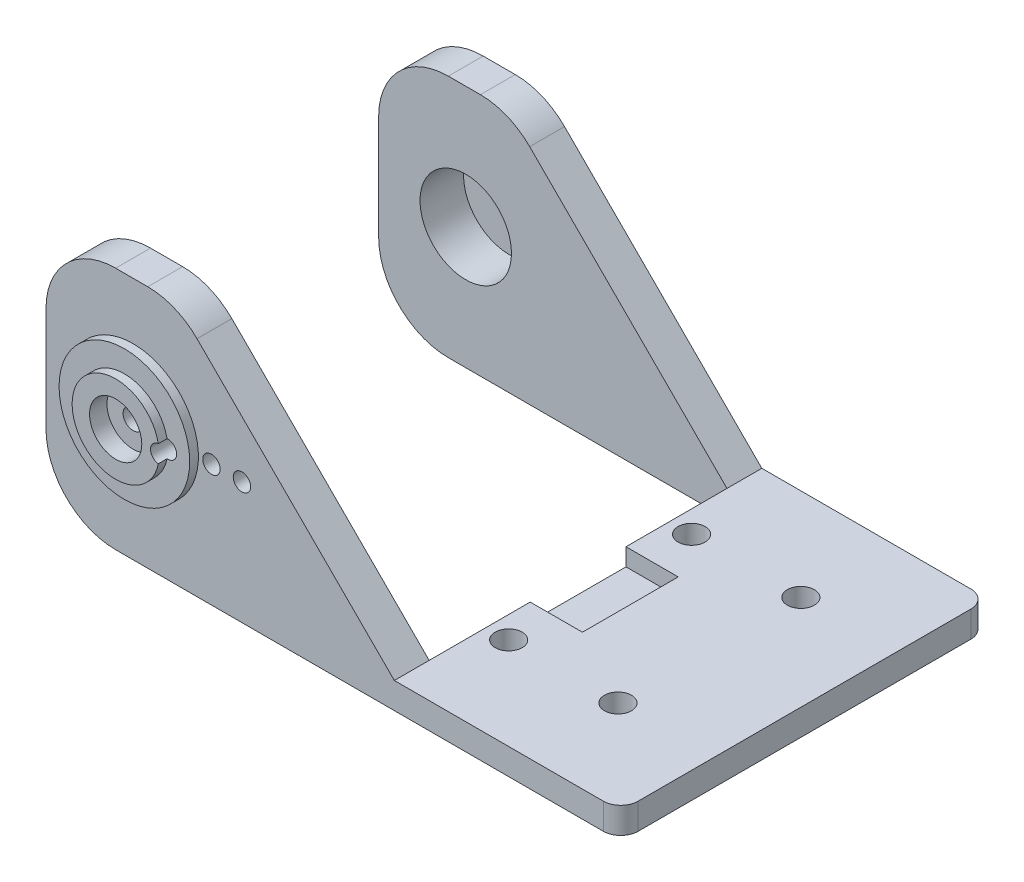
SolidWorks part; units mm, degrees
ref_plane "Front Plane" through (0, 0, 0) normal (0, 0, 1) x (1, 0, 0)
ref_plane "Top Plane" through (0, 0, 0) normal (0, 1, 0) x (1, 0, 0)
ref_plane "Right Plane" through (0, 0, 0) normal (1, 0, 0) x (0, 0, -1)
sketch "Sketch6" plane through (0, 0, 0) normal (0, 0, 1) x (1, 0, 0)
  line L0 (0, 0) -> (15, 0)
  line L1 (15, 0) -> (40, -25)
  line L2 (40, -25) -> (66, -25)
  line L3 (66, -25) -> (66, -28)
  line L4 (66, -28) -> (0, -28)
  line L5 (0, -28) -> (0, 0)
  dimension "D1" = 26
  dimension "D2" = 15
  dimension "D3" = 45
  dimension "D4" = 3
  dimension "D5" = 28
  dimension "D6" = 66
extrude "Perfil lateral" add sketch "Sketch6" along normal blind 42.2
sketch "Sketch7" plane through (0, 0, 0) normal (0, 1, 0) x (1, 0, 0)
  line L1 (0, -4) -> (40, -4)
  line L2 (0, -4) -> (0, -38.2)
  line L3 (0, -38.2) -> (40, -38.2)
  line L4 (40, -4) -> (40, -38.2)
  line L5 (40, -42.2) -> (40, 0) construction
  line L7 (15, 0) -> (0, 0) construction
  line L8 (15, -42.2) -> (0, -42.2) construction
  line L9 (0, -42.2) -> (0, 0) construction
  dimension "D2" = 4
  dimension "D3" = 4
extrude "Corte vertical perfil" cut sketch "Sketch7" against normal through all
sketch "Sketch8" plane through (0, 0, 0) normal (0, 0, 1) x (1, 0, 0)
  line L0 (0, -14) -> (59.2074, -14) construction
  line L1 (0, 0) -> (0, -28) construction
  circle A0 centre (10, -14) radius 6
  point P6 (0, 0)
  dimension "D2" = 12
  dimension "D1" = 10
extrude "soporte al eje giro 1" add sketch "Sketch8" against normal blind 2
sketch "Sketch10" plane through (0, 0, 0) normal (0, 0, -1) x (-1, 0, 0)
  circle A0 centre (-10, -14) radius 7.5
  circle A1 centre (-10, -14) radius 6 construction
  circle A2 centre (-10, -14) radius 6 construction
  point P6 (0, 0)
  point P7 (-8.3, -14)
  dimension "D1" = 15
extrude "soporte al eje giro 2" add sketch "Sketch10" along normal blind 1
sketch "Sketch11" plane through (0, 0, 4) normal (0, 0, 1) x (1, 0, 0)
  circle A0 centre (10, -14) radius 5.25
  circle A2 centre (10, -14) radius 6
  circle A3 centre (10, -14) radius 6 construction
  point P3 (0, 0)
  point P4 (10.5927, -13.7216)
  dimension "D1" = 10.5
  dimension "D2" = 0
extrude "eje giro" cut sketch "Sketch11" against normal blind 5
sketch "Sketch9" plane through (0, 0, 38.2) normal (0, 0, 1) x (1, 0, 0)
  line L0 (0, -14) -> (59.2074, -14) construction
  line L1 (0, -14) -> (10, -14) construction
  line L2 (0, -17.7) -> (10, -17.7)
  line L3 (0, -10.3) -> (10, -10.3)
  line L4 (10, -14) -> (40.3262, -14) construction
  line L5 (10, -10.3) -> (25, -11.9874)
  line L6 (10, -17.7) -> (25, -16.0126)
  line L7 (0, -10.3) -> (0, -17.7)
  circle A1 centre (10, -14) radius 3.7 construction
  circle A2 centre (25, -14) radius 2 construction
  circle A4 centre (10, -14) radius 5.25 construction
  circle A5 centre (10, -14) radius 5.25 construction
  arc A6 (25, -11.9874) -> (25, -16.0126) centre (24.9873, -14) cw
  dimension "D2" = 7.4
  dimension "D3" = 4
  dimension "D4" = 15
extrude "servo horn bed" cut sketch "Sketch9" along normal blind 2.5
sketch "Sketch13" plane through (0, -25, 0) normal (0, 1, 0) x (1, 0, 0)
  line L0 (40, -21.1) -> (66, -21.1) construction
  line L1 (40, -38.2) -> (40, -4) construction
  line L2 (66, -42.2) -> (66, 0) construction
  line L9 (40, -15.5766) -> (40, -26.6234) construction
  circle A0 centre (55.0798, -31.6) radius 1.55
  circle A1 centre (42.5298, -31.6) radius 1.55
  circle A2 centre (42.5298, -10.6) radius 1.55
  circle A3 centre (55.0798, -10.6) radius 1.55
  dimension "D5" = 3.1
  dimension "D1" = 12.55
  dimension "D2" = 21
  dimension "D3" = 21
  dimension "D4" = 10.5
extrude "Huecos base laser" cut sketch "Sketch13" against normal through all
fillet "Fillet1" radius 8 6 edges at (15, 0, 2) (15, 0, 40.2) (0, 0, 40.2) (0, -28, 40.2) (0, -28, 2) (0, 0, 2)
sketch "Sketch14" plane through (0, 0, 42.2) normal (0, 0, 1) x (1, 0, 0)
  circle A2 centre (10, -14) radius 7.5
  circle A3 centre (10, -14) radius 5.25 construction
  circle A4 centre (10, -14) radius 5.25 construction
  point P1 (0, 0)
  dimension "D1" = 15
extrude "Decoracion horn" add sketch "Sketch14" along normal blind 1
sketch "Sketch15" plane through (0, 0, 43.2) normal (0, 0, 1) x (1, 0, 0)
  circle A4 centre (10, -14) radius 7.5 construction
  circle A5 centre (10, -14) radius 7.5 construction
  circle A6 centre (10, -14) radius 5
  dimension "D1" = 10
extrude "Decoracion Horn 2" add sketch "Sketch15" along normal blind 1
sketch "Sketch16" plane through (0, 0, 44.2) normal (0, 0, 1) x (1, 0, 0)
  circle A0 centre (10, -14) radius 3
  dimension "D1" = 6
sketch "Sketch12" plane through (0, 0, 42.2) normal (0, 0, 1) x (1, 0, 0)
  line L0 (10, -14) -> (24.0218, -14) construction
  circle A0 centre (10, -14) radius 5.25 construction
  circle A1 centre (10, -14) radius 5.25 construction
  circle A2 centre (10, -14) radius 1.15
  circle A3 centre (15, -14) radius 1
  circle A4 centre (19, -14) radius 1
  circle A5 centre (22.5, -14) radius 1
  dimension "D1" = 2.3
  dimension "D5" = 2
  dimension "D2" = 5
  dimension "D3" = 9
  dimension "D4" = 12.5
extrude "Tornillos horn" cut sketch "Sketch12" against normal up to surface (1.5 mm away) and the other way through all up to face at (12, -14, 40.7)
extrude "cabeza tornillo horn" cut sketch "Sketch16" against normal up to surface (2 mm away) up to face at (18, -14, 42.2)
sketch "Sketch17" plane through (0, -25, 0) normal (0, 1, 0) x (1, 0, 0)
  line L0 (40, -21.1) -> (66, -21.1) construction
  line L1 (40, -38.2) -> (40, -4) construction
  line L2 (66, -42.2) -> (66, 0) construction
  line L3 (34, -26.6) -> (34, -15.6)
  line L4 (34, -26.6) -> (46, -26.6)
  line L5 (34, -15.6) -> (46, -15.6)
  line L6 (46, -26.6) -> (46, -15.6)
  line L7 (40, -15.6) -> (40, -26.6) construction
  line L8 (34, -21.1) -> (46, -21.1) construction
  dimension "D1" = 11
  dimension "D2" = 12
extrude "Cut-Extrude9" cut sketch "Sketch17" against normal blind 2
fillet "Fillet2" radius 2 2 edges at (66, -26.5, 42.2) (66, -26.5, 0)
